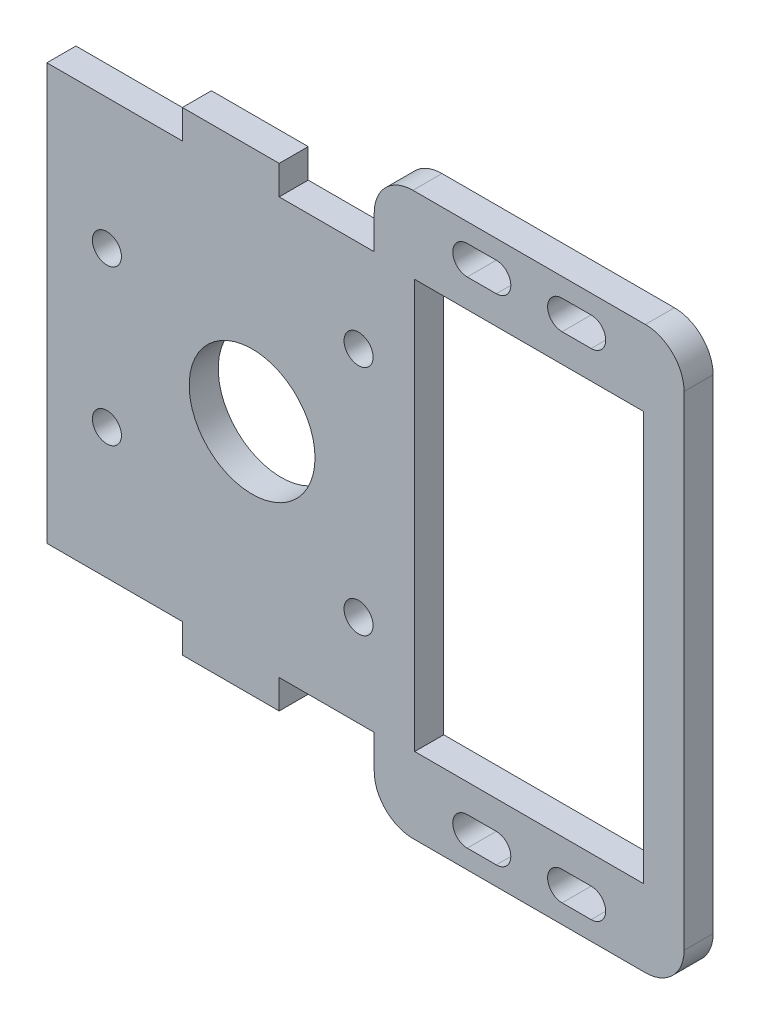
SolidWorks part; units mm, degrees
material "Acrylic (Medium-high impact)"
ref_plane "Front Plane" through (0, 0, 0) normal (0, 0, 1) x (1, 0, 0)
ref_plane "Top Plane" through (0, 0, 0) normal (0, 1, 0) x (1, 0, 0)
ref_plane "Right Plane" through (0, 0, 0) normal (1, 0, 0) x (0, 0, -1)
sketch "Sketch1" plane through (0, 0, 0) normal (0, 0, 1) x (1, 0, 0)
  line L0 (12.62, 29) -> (12.62, 21.5)
  line L1 (-7.2, 21.5) -> (-7.2, 24.5)
  line L2 (-7.2, 24.5) -> (2.8, 24.5)
  line L3 (2.8, 24.5) -> (2.8, 21.5)
  line L4 (-7.2, -21.5) -> (-7.2, -24.5)
  line L5 (-7.2, -24.5) -> (2.8, -24.5)
  line L6 (2.8, -24.5) -> (2.8, -21.5)
  line L7 (-2.2, 24.5) -> (-2.2, -24.5) construction
  line L8 (-7.2, 21.5) -> (-21.2, 21.5)
  line L9 (2.8, -21.5) -> (12.62, -21.5)
  line L10 (-21.2, 21.5) -> (12.62, 21.5) construction
  line L11 (22.2293, 27.05) -> (25.2293, 27.05)
  line L12 (22.2293, 24.05) -> (25.2293, 24.05)
  line L13 (32.0293, 27.05) -> (35.0293, 27.05)
  line L14 (32.0293, 24.05) -> (35.0293, 24.05)
  line L15 (22.2293, -24.05) -> (25.2293, -24.05)
  line L16 (22.2293, -27.05) -> (25.2293, -27.05)
  line L17 (27.1293, 21.125) -> (27.1293, -21.125) construction
  line L18 (16.8, -21.125) -> (16.8, 21.125)
  line L19 (16.8, -21.125) -> (40.45, -21.125)
  line L20 (40.45, -21.125) -> (40.45, 21.125)
  line L21 (16.8, 21.125) -> (40.45, 21.125)
  line L22 (12.62, 21.5) -> (2.8, 21.5)
  line L23 (16.8, 0) -> (40.45, 0) construction
  line L24 (-6.5, 0) -> (6.5, 0) construction
  line L25 (-21.2, 21.5) -> (-21.2, -21.5)
  line L26 (-21.2, -21.5) -> (-7.2, -21.5)
  line L27 (12.62, 29) -> (44.63, 29)
  line L28 (12.62, -29) -> (12.62, -21.5)
  line L29 (44.63, 29) -> (44.63, -29)
  line L30 (12.62, -29) -> (44.63, -29)
  line L31 (32.0293, -24.05) -> (35.0293, -24.05)
  line L32 (32.0293, -27.05) -> (35.0293, -27.05)
  circle A0 centre (-15, -8) radius 1.5
  circle A1 centre (-15, 8) radius 1.5
  circle A2 centre (11, 12) radius 1.5
  circle A3 centre (11, -12) radius 1.5
  arc A4 (25.2293, 24.05) -> (25.2293, 27.05) centre (25.2293, 25.55) ccw
  arc A5 (35.0293, 24.05) -> (35.0293, 27.05) centre (35.0293, 25.55) ccw
  arc A6 (25.2293, -27.05) -> (25.2293, -24.05) centre (25.2293, -25.55) ccw
  circle A7 centre (0, 0) radius 6.5
  circle A8 centre (27.1293, 10.8) radius 9 construction
  arc A9 (22.2293, 27.05) -> (22.2293, 24.05) centre (22.2293, 25.55) ccw
  arc A10 (32.0293, 27.05) -> (32.0293, 24.05) centre (32.0293, 25.55) ccw
  arc A11 (22.2293, -24.05) -> (22.2293, -27.05) centre (22.2293, -25.55) ccw
  arc A12 (32.0293, -24.05) -> (32.0293, -27.05) centre (32.0293, -25.55) ccw
  circle A13 centre (0, 0) radius 29.2 construction
  arc A14 (35.0293, -27.05) -> (35.0293, -24.05) centre (35.0293, -25.55) ccw
  point P20 (-4.29, 21.5)
  dimension "D4" = 3
  dimension "D7" = 10
  dimension "D8" = 8
  dimension "D12" = 51.1
  dimension "D15" = 2.2
  dimension "D18" = 9.8
  dimension "D13" = 4.18
  dimension "D20" = 13
  dimension "D28" = 10.8
  dimension "D10" = 11
  dimension "D11" = 24
  dimension "D21" = 18
  dimension "D23" = 58.4
  dimension "D3" = 42.25
  dimension "D5" = 15
  dimension "D6" = 3
  dimension "D9" = 19
  dimension "D14" = 4.18
  dimension "D16" = 3
  dimension "D19" = 23.65
  dimension "D22" = 58
  dimension "D24" = 43
  dimension "D26" = 38
extrude "Boss-Extrude1" add sketch "Sketch1" along normal blind 3
sketch "Sketch2" plane through (0, 0, 3) normal (0, 0, 1) x (1, 0, 0)
  line L0 (40.45, 21.125) -> (16.8, 21.125) construction
  line L1 (27.875, 27.125) -> (29.375, 27.125)
  line L2 (27.875, 27.125) -> (27.875, 21.125)
  line L3 (27.875, 21.125) -> (29.375, 21.125)
  line L4 (29.375, 27.125) -> (29.375, 21.125)
  line L5 (29.375, -27.125) -> (29.375, -21.125)
  line L6 (28.625, -21.125) -> (28.625, 21.125) construction
  line L7 (16.8, -21.125) -> (40.45, -21.125) construction
  line L8 (16.8, 0) -> (40.45, 0) construction
  line L9 (16.8, 21.125) -> (16.8, -21.125) construction
  line L10 (40.45, -21.125) -> (40.45, 21.125) construction
  line L11 (27.875, -21.125) -> (29.375, -21.125)
  line L12 (27.875, -27.125) -> (27.875, -21.125)
  line L13 (27.875, -27.125) -> (29.375, -27.125)
  dimension "D1" = 1.5
  dimension "D2" = 6
fillet "Fillet1" radius 4 4 edges at (44.63, 29, 1.5) (12.62, 29, 1.5) (12.62, -29, 1.5) (44.63, -29, 1.5)
sketch "Sketch3" plane through (0, 0, 3) normal (0, 0, 1) x (1, 0, 0)
  line L0 (0, 0) -> (27.1293, 10.8) construction
  line L1 (24.2793, 9.8633) -> (24.2793, 5.3) construction
  line L2 (24.2793, 5.3) -> (29.9793, 5.3) construction
  line L3 (29.9793, 5.3) -> (29.9793, 9.8633) construction
  line L4 (27.1293, 10.8) -> (27.1293, 5.3) construction
  circle A0 centre (0, 0) radius 20.25
  circle A1 centre (27.1293, 10.8) radius 9.75
  circle A2 centre (27.1293, 10.8) radius 3 construction
  point P0 (27.1293, 10.8)
  point P12 (27.1293, 7.8)
  dimension "D1" = 19.5
  dimension "D2" = 6
  dimension "D5" = 40.5
  dimension "D3" = 5.7
  dimension "D4" = 2.5
equation "\"D19@Sketch1\"=20.2+\"print_free@Parameters@Parameters.SLDPRT\"+\"LinkADist@Parameters@Parameters.SLDPRT\""
equation "\"D3@Sketch1\"= 41.8 + \"print_free@Parameters@Parameters.SLDPRT\""
equation "\"D23@Sketch1\"=\"CenterDist1@Parameters@Parameters.SLDPRT\"*2"
equation "\"D16@Sketch1\"=\"LinkADist@Parameters@Parameters.SLDPRT\""
